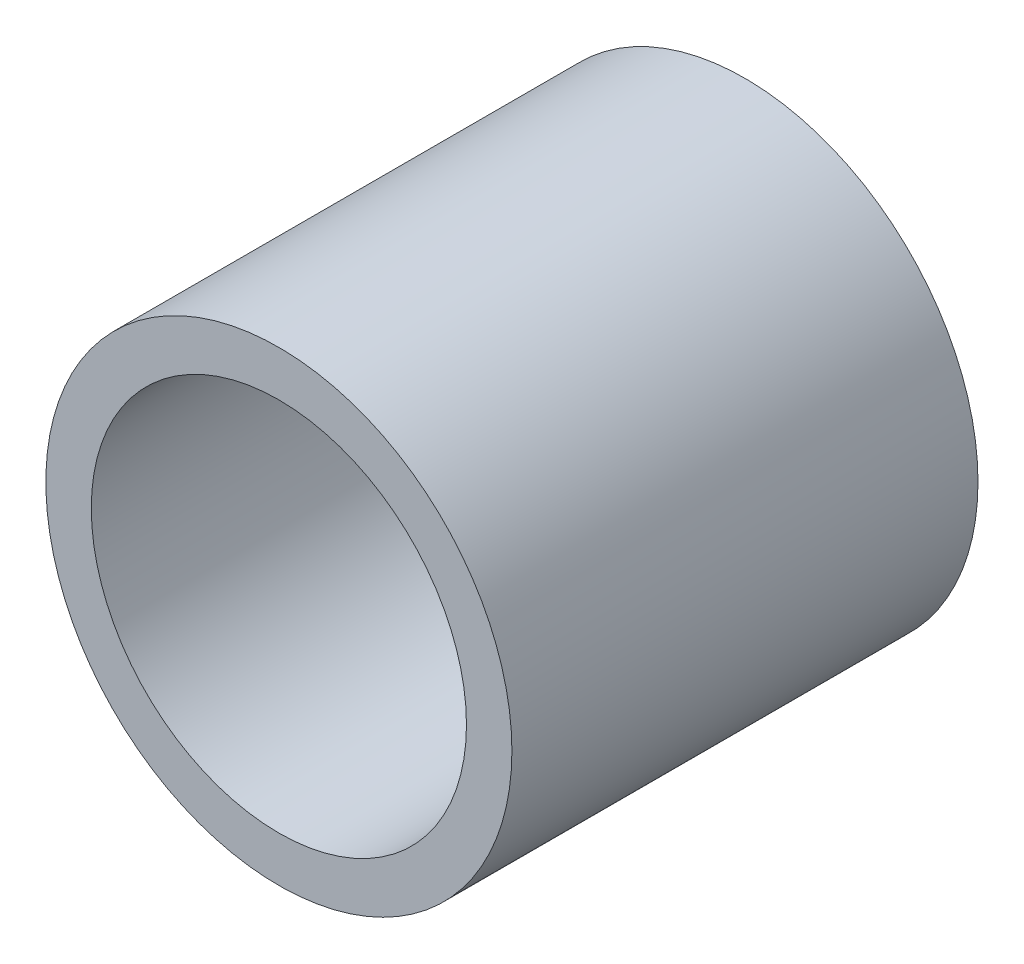
SolidWorks part; units mm, degrees
material "Brass"
ref_plane "Front Plane" through (0, 0, 0) normal (0, 0, 1) x (1, 0, 0)
ref_plane "Top Plane" through (0, 0, 0) normal (0, 1, 0) x (1, 0, 0)
ref_plane "Right Plane" through (0, 0, 0) normal (1, 0, 0) x (0, 0, -1)
sketch "Sketch1" plane through (0, 0, 0) normal (0, 0, 1) x (1, 0, 0)
  circle A0 centre (0, 0) radius 5
  circle A1 centre (0, 0) radius 4.025
  dimension "D1" = 10
  dimension "D2" = 8.05
extrude "Boss-Extrude1" add sketch "Sketch1" along normal blind 10
